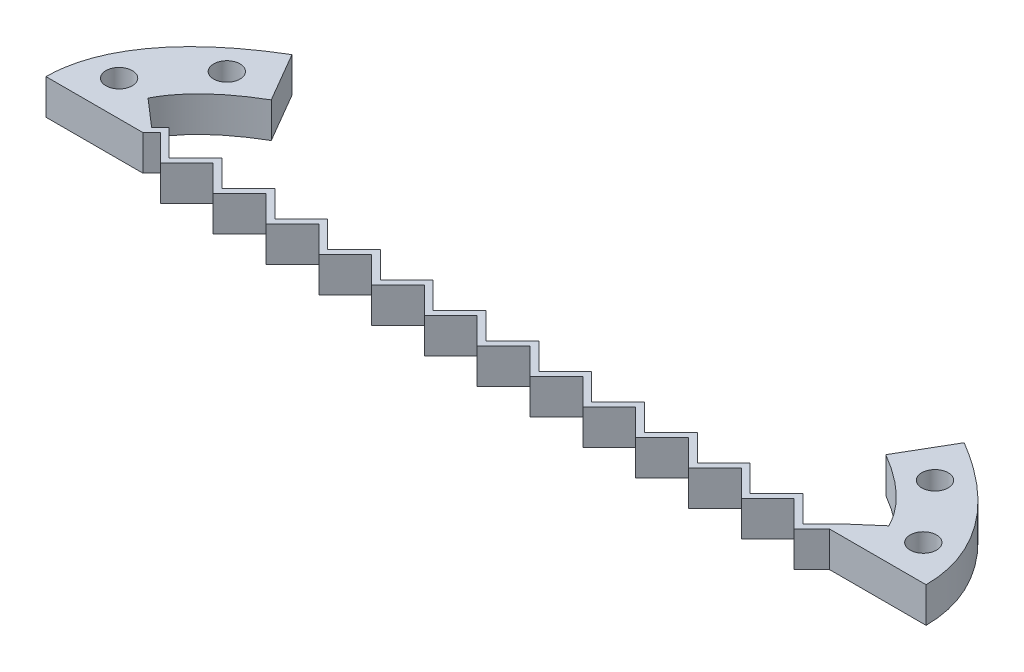
SolidWorks part; units mm, degrees
ref_plane "Спереди" through (0, 0, 0) normal (0, 0, 1) x (1, 0, 0)
ref_plane "Сверху" through (0, 0, 0) normal (0, 1, 0) x (1, 0, 0)
ref_plane "Справа" through (0, 0, 0) normal (1, 0, 0) x (0, 0, -1)
sketch "Эскиз1" plane through (0, 0, 0) normal (0, 1, 0) x (1, 0, 0)
  line L0 (-43, 0) -> (-50, 0)
  line L1 (0, 0) -> (-60, 0) construction
  line L2 (0, 0) -> (-61.87, 5.4129) construction
  line L3 (0, 0) -> (-70.3284, 18.8444) construction
  line L4 (0, 0) -> (-80.7735, 29.3992) construction
  line L5 (-38.1898, 16.1364) -> (-34.9127, 10.5078)
  line L6 (0, 0) -> (0, 54.5279) construction
  line L7 (-43, 0) -> (-39, 0)
  line L8 (-39, 0) -> (-38, 1)
  line L9 (-39, 1) -> (-42.0905, 3.6824)
  line L10 (43, 0) -> (39, 0)
  line L11 (-38, 2) -> (-39, 1)
  line L12 (-35, -1) -> (-38, 2)
  line L13 (39, 1) -> (42.0905, 3.6824)
  line L14 (-33, 1) -> (-35, -1)
  line L15 (-35, -2) -> (-38, 1)
  line L16 (43, 0) -> (50, 0)
  line L17 (-33, 0) -> (-35, -2)
  line L18 (38.1898, 16.1364) -> (34.9127, 10.5078)
  line L19 (-27, 0) -> (-29, -2)
  line L20 (-27, 1) -> (-29, -1)
  line L21 (-29, -1) -> (-32, 2)
  line L22 (-29, -2) -> (-32, 1)
  line L23 (-33, 0) -> (-32, 1)
  line L24 (-32, 2) -> (-33, 1)
  line L25 (-21, 0) -> (-23, -2)
  line L26 (-21, 1) -> (-23, -1)
  line L27 (-23, -1) -> (-26, 2)
  line L28 (-23, -2) -> (-26, 1)
  line L29 (-27, 0) -> (-26, 1)
  line L30 (-26, 2) -> (-27, 1)
  line L31 (-15, 0) -> (-17, -2)
  line L32 (-15, 1) -> (-17, -1)
  line L33 (-17, -1) -> (-20, 2)
  line L34 (-17, -2) -> (-20, 1)
  line L35 (-21, 0) -> (-20, 1)
  line L36 (-20, 2) -> (-21, 1)
  line L37 (-9, 0) -> (-11, -2)
  line L38 (-9, 1) -> (-11, -1)
  line L39 (-11, -1) -> (-14, 2)
  line L40 (-11, -2) -> (-14, 1)
  line L41 (-15, 0) -> (-14, 1)
  line L42 (-14, 2) -> (-15, 1)
  line L43 (-3, 0) -> (-5, -2)
  line L44 (-3, 1) -> (-5, -1)
  line L45 (-5, -1) -> (-8, 2)
  line L46 (-5, -2) -> (-8, 1)
  line L47 (-9, 0) -> (-8, 1)
  line L48 (-8, 2) -> (-9, 1)
  line L49 (3, 0) -> (1, -2)
  line L50 (3, 1) -> (1, -1)
  line L51 (1, -1) -> (-2, 2)
  line L52 (1, -2) -> (-2, 1)
  line L53 (-3, 0) -> (-2, 1)
  line L54 (-2, 2) -> (-3, 1)
  line L55 (9, 0) -> (7, -2)
  line L56 (9, 1) -> (7, -1)
  line L57 (7, -1) -> (4, 2)
  line L58 (7, -2) -> (4, 1)
  line L59 (3, 0) -> (4, 1)
  line L60 (4, 2) -> (3, 1)
  line L61 (15, 0) -> (13, -2)
  line L62 (15, 1) -> (13, -1)
  line L63 (13, -1) -> (10, 2)
  line L64 (13, -2) -> (10, 1)
  line L65 (9, 0) -> (10, 1)
  line L66 (10, 2) -> (9, 1)
  line L67 (21, 0) -> (19, -2)
  line L68 (21, 1) -> (19, -1)
  line L69 (19, -1) -> (16, 2)
  line L70 (19, -2) -> (16, 1)
  line L71 (15, 0) -> (16, 1)
  line L72 (16, 2) -> (15, 1)
  line L73 (27, 0) -> (25, -2)
  line L74 (27, 1) -> (25, -1)
  line L75 (25, -1) -> (22, 2)
  line L76 (25, -2) -> (22, 1)
  line L77 (21, 0) -> (22, 1)
  line L78 (22, 2) -> (21, 1)
  line L79 (33, 0) -> (31, -2)
  line L80 (33, 1) -> (31, -1)
  line L81 (31, -1) -> (28, 2)
  line L82 (31, -2) -> (28, 1)
  line L83 (27, 0) -> (28, 1)
  line L84 (28, 2) -> (27, 1)
  line L85 (39, 0) -> (37, -2)
  line L86 (39, 1) -> (37, -1)
  line L87 (37, -1) -> (34, 2)
  line L88 (37, -2) -> (34, 1)
  line L89 (33, 0) -> (34, 1)
  line L90 (34, 2) -> (33, 1)
  circle A0 centre (-45.6893, 3.9973) radius 1.5
  circle A1 centre (-40.2324, 10.7802) radius 1.5
  circle A2 centre (45.6893, 3.9973) radius 1.5
  circle A3 centre (40.2324, 10.7802) radius 1.5
  ellipse E0 centre (0, 0) end of major axis (50, 0) minor radius 25 construction
  ellipse E1 centre (0, 0) end of major axis (43, 0) minor radius 18 construction
  ellipse E2 centre (0, 0) end of major axis (43, 0) minor radius 18 (34.9127, 10.5078) -> (42.0905, 3.6824) cw
  ellipse E3 centre (0, 0) end of major axis (50, 0) minor radius 25 (-38.1898, 16.1364) -> (-50, 0) ccw
  ellipse E4 centre (0, 0) end of major axis (46.5, 0) minor radius 21.5 construction
  ellipse E5 centre (0, 0) end of major axis (-43, 0) minor radius 18 (-34.9127, 10.5078) -> (-42.0905, 3.6824) ccw
  ellipse E6 centre (0, 0) end of major axis (50, 0) minor radius 25 (0, 25) -> (38.1898, 16.1364) ccw
  dimension "D7" = 20
  dimension "D8" = 4
  dimension "D4" = 3
  dimension "D13" = 3
  dimension "D1" = 100
  dimension "D2" = 50
  dimension "D3" = 7
  dimension "D5" = 5
  dimension "D6" = 15
  dimension "D9" = 1
  dimension "D10" = 1
  dimension "D11" = 1
  dimension "D12" = 13
extrude "Бобышка-Вытянуть1" add sketch "Эскиз1" along normal blind 4 contours L16 E6 L18 E2 L13 L86 L87 L90 L80 L81 L84 L74 L75 L78 L68 L69 L72 L62 L63 L66 L56 L57 L60 L50 L51 L54 L44 L45 L48 L38 L39 L42 L32 L33 L36 L26 L27 L30 L20 L21 L24 L14 L12 L11 L9 E5 L5 E3 L0 L7 L8
